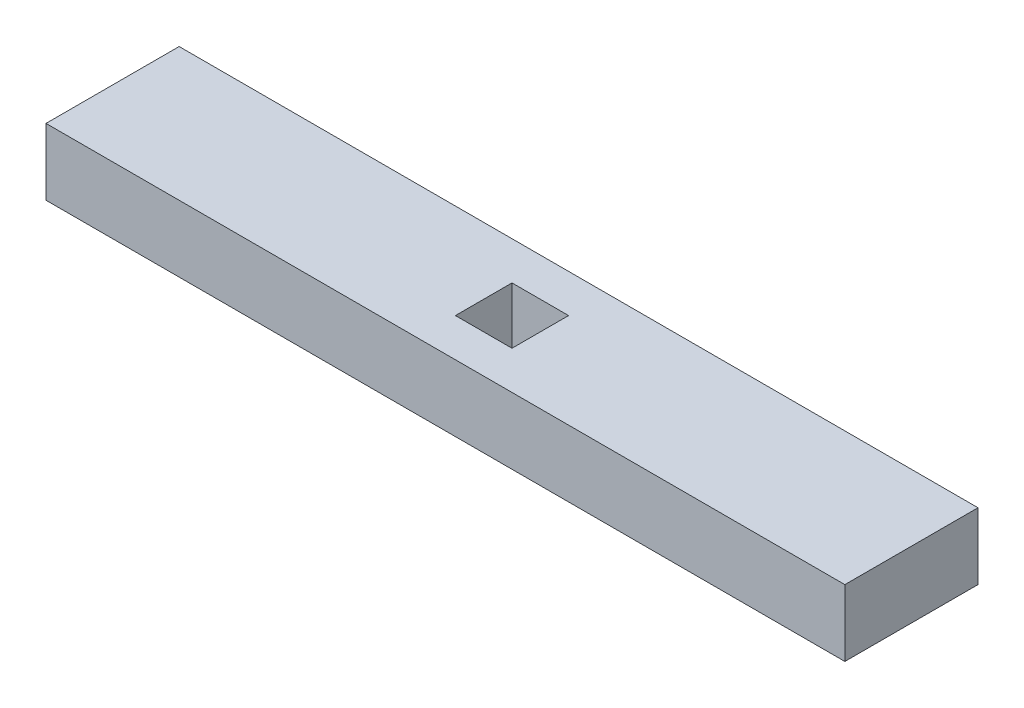
SolidWorks part; units mm, degrees
ref_plane "前视基准面" through (0, 0, 0) normal (0, 0, 1) x (1, 0, 0)
ref_plane "上视基准面" through (0, 0, 0) normal (0, 1, 0) x (1, 0, 0)
ref_plane "右视基准面" through (0, 0, 0) normal (1, 0, 0) x (0, 0, -1)
sketch "草图2" plane through (0, 0, 0) normal (0, 1, 0) x (1, 0, 0)
  line L1 (2.125, 2.125) -> (-2.125, 2.125)
  line L2 (2.125, 2.125) -> (2.125, -2.125)
  line L3 (2.125, -2.125) -> (-2.125, -2.125)
  line L4 (-2.125, 2.125) -> (-2.125, -2.125)
  line L5 (2.125, 2.125) -> (-2.125, -2.125) construction
  line L6 (2.125, -2.125) -> (-2.125, 2.125) construction
  line L7 (30, 5) -> (-30, 5)
  line L8 (30, 5) -> (30, -5)
  line L9 (30, -5) -> (-30, -5)
  line L10 (-30, 5) -> (-30, -5)
  line L11 (30, 5) -> (-30, -5) construction
  line L12 (30, -5) -> (-30, 5) construction
  point P0 (0, 0)
  point P6 (0, 0)
extrude "凸台-拉伸1" add sketch "草图2" along normal blind 5
